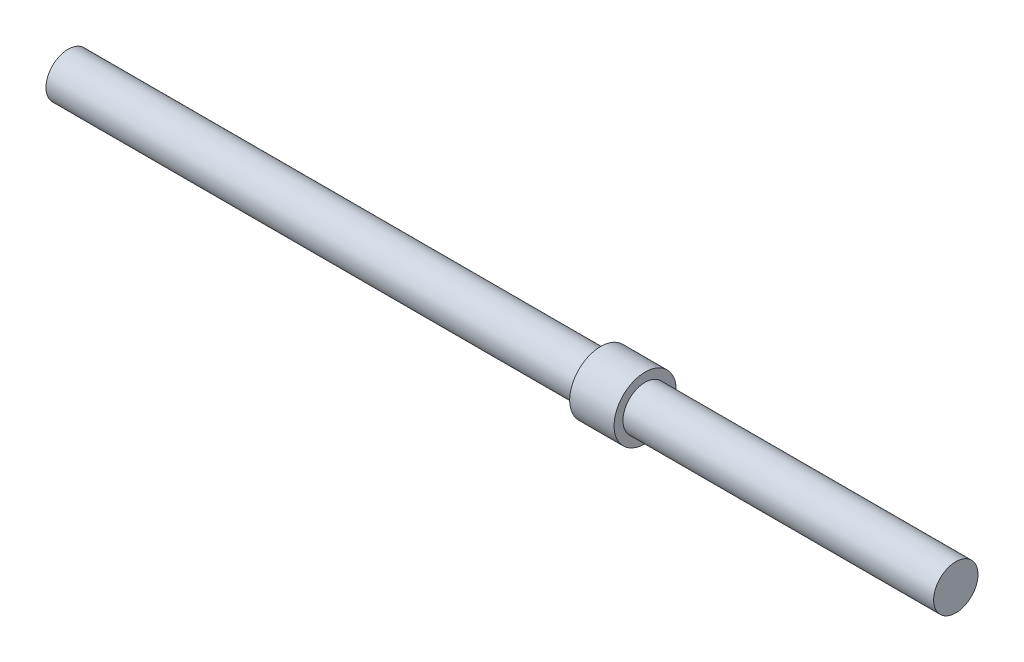
SolidWorks part; units mm, degrees
material "Cast Alloy Steel"
ref_plane "Front Plane" through (0, 0, 0) normal (0, 0, 1) x (1, 0, 0)
ref_plane "Top Plane" through (0, 0, 0) normal (0, 1, 0) x (1, 0, 0)
ref_plane "Right Plane" through (0, 0, 0) normal (1, 0, 0) x (0, 0, -1)
sketch "Sketch1" plane through (0, 0, 0) normal (1, 0, 0) x (0, 0, -1)
  circle A0 centre (0, 0) radius 5
  dimension "D1" = 10
extrude "Boss-Extrude1" add sketch "Sketch1" along normal mid plane 200
sketch "Sketch2" plane through (100, 0, 0) normal (1, 0, 0) x (0, 0, -1)
  circle A0 centre (0, 0) radius 7
  dimension "D1" = 14
extrude "Boss-Extrude2" add sketch "Sketch2" against normal blind 10 from offset 70
